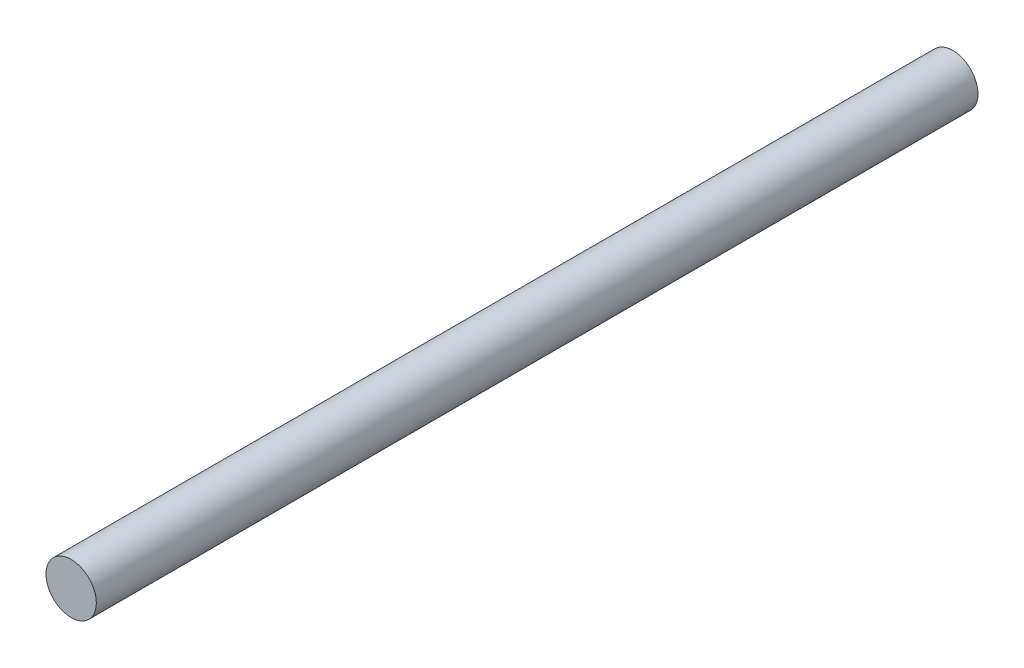
SolidWorks part; units mm, degrees
ref_plane "Plan de face" through (0, 0, 0) normal (0, 0, 1) x (1, 0, 0)
ref_plane "Plan de dessus" through (0, 0, 0) normal (0, 1, 0) x (1, 0, 0)
ref_plane "Plan de droite" through (0, 0, 0) normal (1, 0, 0) x (0, 0, -1)
sketch "Esquisse1" plane through (0, 0, 0) normal (0, 0, 1) x (1, 0, 0)
  circle A0 centre (0, 0) radius 2
  dimension "D1" = 4
extrude "Boss.-Extru.1" add sketch "Esquisse1" along normal blind 70
